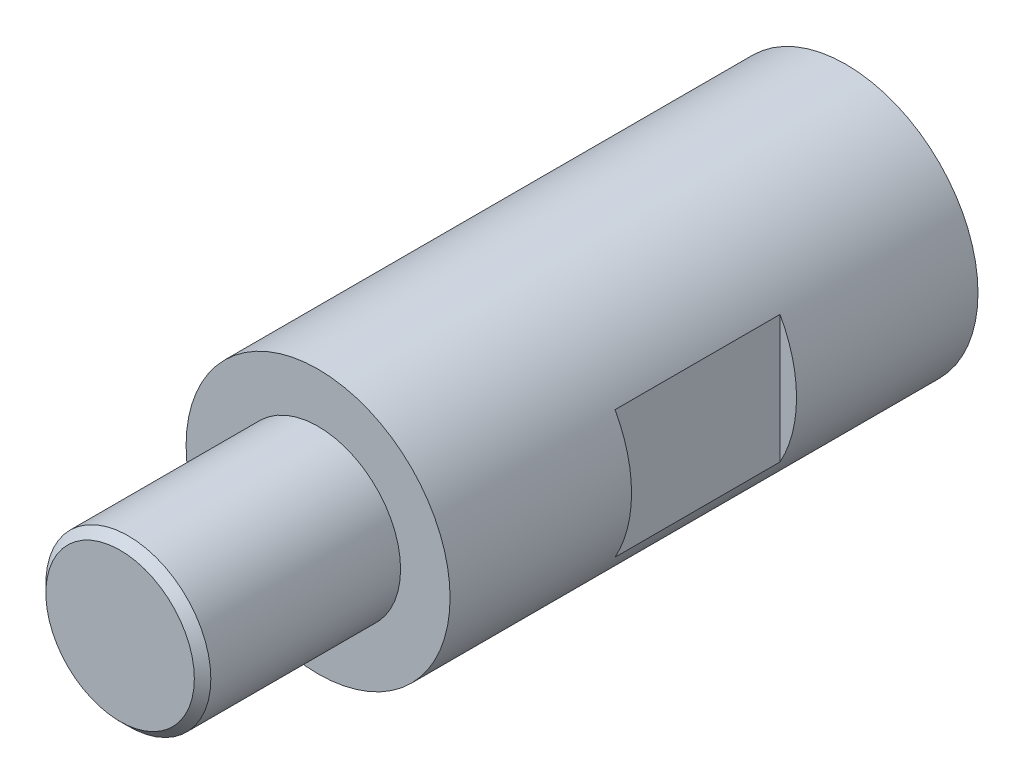
SolidWorks part; units mm, degrees
ref_plane "前视基准面" through (0, 0, 0) normal (0, 0, 1) x (1, 0, 0)
ref_plane "上视基准面" through (0, 0, 0) normal (0, 1, 0) x (1, 0, 0)
ref_plane "右视基准面" through (0, 0, 0) normal (1, 0, 0) x (0, 0, -1)
sketch "草图1" plane through (0, 0, 0) normal (0, 0, 1) x (1, 0, 0)
  circle A0 centre (0, 0) radius 8
  dimension "D1" = 16
extrude "拉伸1" add sketch "草图1" along normal blind 32
sketch "草图2" plane through (0, 0, 0) normal (0, 1, 0) x (1, 0, 0)
  line L0 (-8, 0) -> (-8, -32) construction
  line L1 (-8, -11) -> (-7, -11)
  line L2 (-8, -11) -> (-8, -21)
  line L3 (-8, -21) -> (-7, -21)
  line L4 (-7, -11) -> (-7, -21)
  line L5 (8, -32) -> (8, 0) construction
  line L6 (8, -11) -> (7, -11)
  line L7 (8, -11) -> (8, -21)
  line L8 (8, -21) -> (7, -21)
  line L9 (7, -11) -> (7, -21)
  line L10 (8, 0) -> (-8, 0) construction
  dimension "D1" = 10
  dimension "D2" = 10
  dimension "D3" = 14
  dimension "D4" = 1
  dimension "D5" = 11
  dimension "D6" = 11
extrude "拉伸2" cut sketch "草图2" against normal mid plane 18.5
hole_wizard "M8 螺纹孔1" positions "3D草图1" profile "草图3" tap size "M8" standard "GB"
sketch3d "3D草图1"
  point P1 (0, 0, 0)
sketch "草图3" plane through (0, 0, 0) normal (1, 0, 0) x (0, 1, 0)
  line L0 (0, 0) -> (0, 21.7929)
  line L1 (0, 21.7929) -> (3.4, 19.75)
  line L2 (3.4, 19.75) -> (3.4, 16)
  line L3 (3.4, 16) -> (4, 16)
  line L4 (4, 16) -> (4, 0)
  line L5 (4, 0) -> (0, 0)
  line L10 (0, 21.7929) -> (-3.4, 19.75) construction
  line L11 (0, -6.35) -> (0, 107.95) construction
  dimension "螺纹孔钻头直径" = 6.8
  dimension "螺纹孔钻头深度" = 19.75
  dimension "螺纹主直径" = 8
  dimension "螺纹深度" = 16
  dimension "导头角度" = 118
sketch "草图4" plane through (0, 0, 32) normal (0, 0, 1) x (1, 0, 0)
  circle A0 centre (0, 0) radius 5
  dimension "D1" = 10
extrude "拉伸3" add sketch "草图4" along normal blind 12
cosmetic thread "装饰螺纹线1" parameters "D1"=10.5, "D2"=8.6
chamfer "倒角1" distance 0.5 angle 45 1 edges at (5, 0, 44)
sketch "草图5" plane through (0, 0, 0) normal (1, 0, 0) x (0, 0, -1)
  line L0 (-32, 5) -> (-32, -5) construction
  line L1 (-32, 4.5) -> (-33.5, 4.5)
  line L2 (-32, 4.5) -> (-32, 4.43)
  line L3 (-32, 4.43) -> (-33.5, 4.43)
  line L4 (-33.5, 4.5) -> (-33.5, 4.43)
  line L5 (-32, 5) -> (-43.5, 5) construction
  dimension "D1" = 0.5
  dimension "D2" = 1.5
revolve "切除-旋转1" cut sketch "草图5" angle 360 about axis through (0, 0, 32) along (0, 0, -1)
